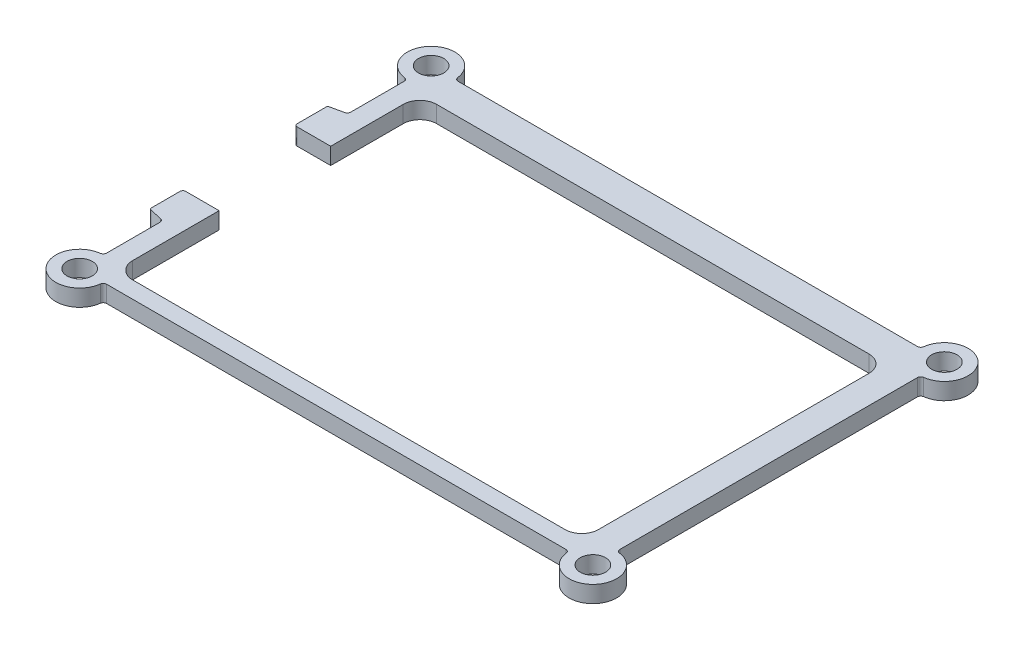
SolidWorks part; units mm, degrees
material "Balsa"
ref_plane "Front Plane" through (0, 0, 0) normal (0, 0, 1) x (1, 0, 0)
ref_plane "Top Plane" through (0, 0, 0) normal (0, 1, 0) x (1, 0, 0)
ref_plane "Right Plane" through (0, 0, 0) normal (1, 0, 0) x (0, 0, -1)
sketch "Sketch3" plane through (0, 0, 0) normal (0, 1, 0) x (1, 0, 0)
  line L0 (46, 0) -> (46, -63) construction
  line L5 (0, -4.265) -> (0, -58.735)
  line L6 (3.2, -3.25) -> (88.8, -3.25) construction
  line L7 (3.2, -3.25) -> (3.2, -59.75) construction
  line L8 (3.2, -59.75) -> (88.8, -59.75) construction
  line L9 (88.8, -3.25) -> (88.8, -59.75) construction
  line L10 (3.2, -3.25) -> (88.8, -59.75) construction
  line L11 (3.2, -59.75) -> (88.8, -3.25) construction
  line L12 (4.265, 0) -> (87.735, 0)
  line L13 (4.265, -63) -> (87.735, -63)
  line L14 (92, -4.265) -> (92, -58.735)
  circle A0 centre (0, 0) radius 2.265
  circle A1 centre (92, 0) radius 2.265
  circle A2 centre (92, -63) radius 2.265
  circle A3 centre (0, -63) radius 2.265
  arc A4 (4.265, 0) -> (0, -4.265) centre (0, 0) ccw
  arc A5 (92, -4.265) -> (87.735, 0) centre (92, 0) ccw
  arc A6 (87.735, -63) -> (92, -58.735) centre (92, -63) ccw
  arc A7 (0, -58.735) -> (4.265, -63) centre (0, -63) ccw
  point P7 (46, -31.5)
  dimension "D5" = 4.53
  dimension "D6" = 2
  dimension "D1" = 92
  dimension "D2" = 63
  dimension "D3" = 85.6
  dimension "D4" = 56.5
extrude "Boss-Extrude2" add sketch "Sketch3" along normal blind 3
sketch "Sketch4" plane through (0, 3, 0) normal (0, 1, 0) x (1, 0, 0)
  line L0 (0, -31.5) -> (92, -31.5) construction
  line L1 (0, -4.265) -> (0, -58.735) construction
  line L2 (92, -58.735) -> (92, -4.265) construction
  line L4 (0, -21.5) -> (6.5, -21.5)
  line L5 (0, -21.5) -> (0, -41.5)
  line L6 (0, -41.5) -> (6.5, -41.5)
  line L7 (6.5, -21.5) -> (6.5, -41.5)
  point P11 (0, -31.5)
  dimension "D1" = 20
  dimension "D2" = 6.5
extrude "Cut-Extrude1" cut sketch "Sketch4" against normal blind 3
sketch "Sketch5" plane through (0, 3, 0) normal (0, 1, 0) x (1, 0, 0)
  line L0 (0, -4.265) -> (0, -21.5) construction
  line L1 (0, -21.5) -> (-2.5, -21.5)
  line L2 (0, -21.5) -> (0, -14.9)
  line L4 (-3, -21) -> (-3, -15.8)
  line L5 (-2.7, -15.5) -> (0, -14.9)
  line L6 (6.5, -31.5) -> (-22.1385, -31.5) construction
  line L7 (6.5, -41.5) -> (6.5, -21.5) construction
  line L8 (-3, -42) -> (-3, -47.2)
  line L9 (0, -41.5) -> (-2.5, -41.5)
  line L10 (0, -41.5) -> (0, -48.1)
  line L11 (-2.7, -47.5) -> (0, -48.1)
  arc A0 (-3, -21) -> (-2.5, -21.5) centre (-2.5, -21) ccw
  arc A1 (-3, -15.8) -> (-2.7, -15.5) centre (-2.7, -15.8) cw
  arc A2 (-3, -47.2) -> (-2.7, -47.5) centre (-2.7, -47.2) ccw
  arc A3 (-3, -42) -> (-2.5, -41.5) centre (-2.5, -42) cw
  point P7 (-3, -21.5)
  point P10 (-3, -15.5)
  dimension "D3" = 0.5
  dimension "D4" = 0.3
  dimension "D1" = 6
  dimension "D2" = 3
  dimension "D5" = 6.6
extrude "Boss-Extrude3" add sketch "Sketch5" against normal blind 3
fillet "Fillet1" radius 0.6 12 edges at (6.5, 1.5, 21.5) (6.5, 1.5, 41.5) (0, 1.5, 48.1) (4.265, 1.5, 63) (0, 1.5, 58.735) (87.735, 1.5, 63) (92, 1.5, 58.735) (92, 1.5, 4.265) (87.735, 1.5, 0) (4.265, 1.5, 0) (0, 1.5, 4.265) (0, 1.5, 14.9)
sketch "Sketch7" plane through (0, 3, 0) normal (0, 1, 0) x (1, 0, 0)
  line L0 (45.25, -5.5) -> (45.25, -60) construction
  line L1 (87.1721, 0) -> (4.8279, 0) construction
  line L2 (4.8279, -63) -> (87.1721, -63) construction
  line L3 (0, -4.8279) -> (0, -14.4187) construction
  line L4 (6.5, -5.5) -> (84, -5.5)
  line L5 (3.5, -8.5) -> (3.5, -57)
  line L6 (6.5, -60) -> (84, -60)
  line L7 (87, -8.5) -> (87, -57)
  line L8 (3.5, -5.5) -> (87, -60) construction
  line L9 (3.5, -60) -> (87, -5.5) construction
  line L10 (92, -58.1721) -> (92, -4.8279) construction
  arc A0 (6.5, -60) -> (3.5, -57) centre (6.5, -57) cw
  arc A1 (84, -60) -> (87, -57) centre (84, -57) ccw
  arc A2 (87, -8.5) -> (84, -5.5) centre (84, -8.5) ccw
  arc A3 (3.5, -8.5) -> (6.5, -5.5) centre (6.5, -8.5) cw
  point P6 (45.25, -32.75)
  dimension "D5" = 3
  dimension "D1" = 3
  dimension "D2" = 3.5
  dimension "D3" = 5.5
  dimension "D4" = 5
extrude "Cut-Extrude2" cut sketch "Sketch7" against normal blind 3
